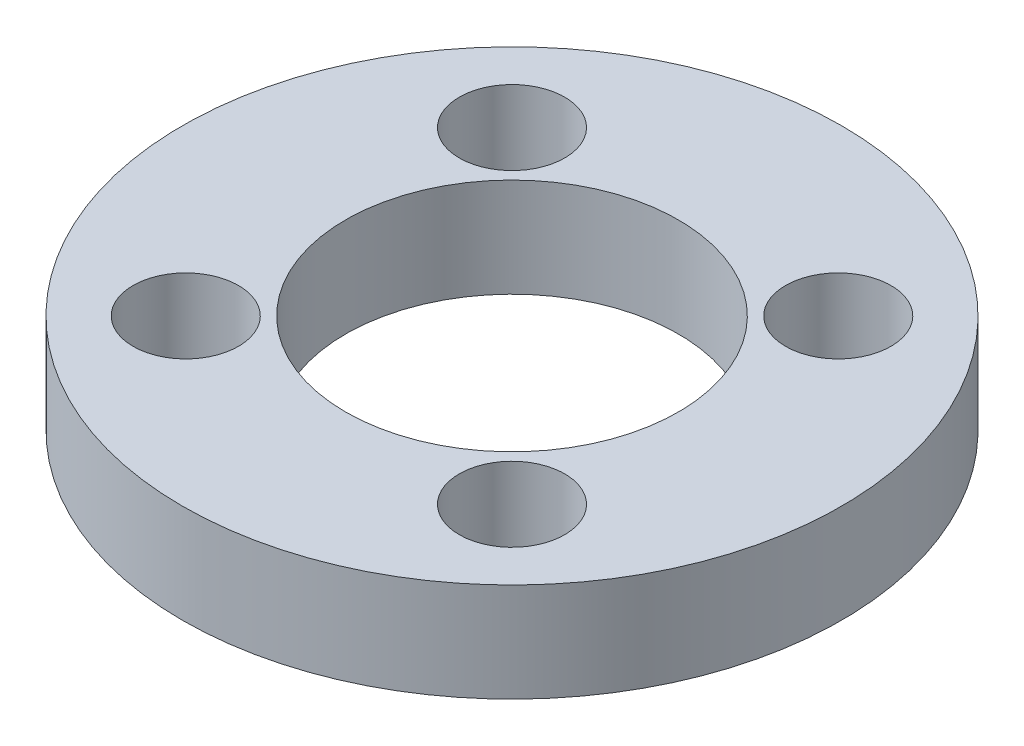
SolidWorks part; units mm, degrees
material "PMMA"
ref_plane "前视基准面" through (0, 0, 0) normal (0, 0, 1) x (1, 0, 0)
ref_plane "上视基准面" through (0, 0, 0) normal (0, 1, 0) x (1, 0, 0)
ref_plane "右视基准面" through (0, 0, 0) normal (1, 0, 0) x (0, 0, -1)
sketch "草图1" plane through (0, 0, 0) normal (0, 1, 0) x (1, 0, 0)
  line L1 (-4.9497, -4.9497) -> (4.9497, -4.9497) construction
  line L2 (-4.9497, -4.9497) -> (-4.9497, 4.9497) construction
  line L3 (-4.9497, 4.9497) -> (4.9497, 4.9497) construction
  line L4 (4.9497, -4.9497) -> (4.9497, 4.9497) construction
  line L5 (-4.9497, -4.9497) -> (4.9497, 4.9497) construction
  line L6 (-4.9497, 4.9497) -> (4.9497, -4.9497) construction
  circle A0 centre (0, 0) radius 5.05
  circle A1 centre (4.9497, 4.9497) radius 1.6
  circle A2 centre (-4.9497, 4.9497) radius 1.6
  circle A3 centre (-4.9497, -4.9497) radius 1.6
  circle A4 centre (4.9497, -4.9497) radius 1.6
  circle A5 centre (0, 0) radius 10
  dimension "D1" = 10.1
  dimension "D2" = 3.2
  dimension "D4" = 20
  dimension "D3" = 14
extrude "凸台-拉伸1" add sketch "草图1" along normal blind 3
